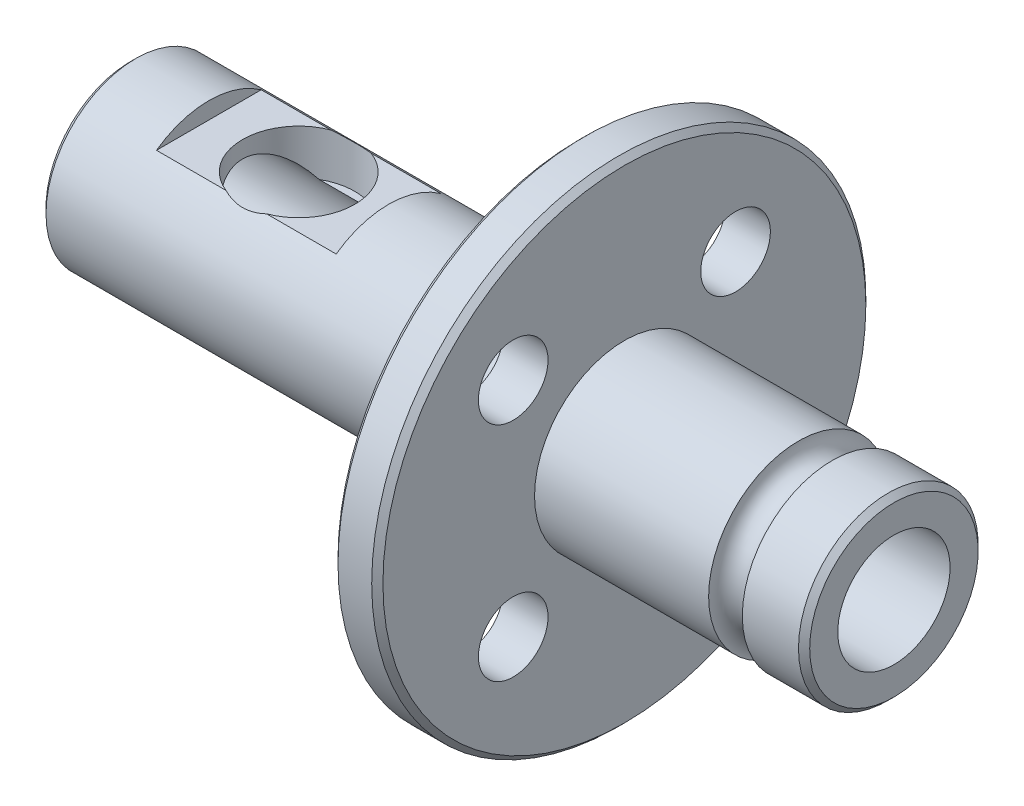
SolidWorks part; units mm, degrees
ref_plane "Front Plane" through (0, 0, 0) normal (0, 0, 1) x (1, 0, 0)
ref_plane "Top Plane" through (0, 0, 0) normal (0, 1, 0) x (1, 0, 0)
ref_plane "Right Plane" through (0, 0, 0) normal (1, 0, 0) x (0, 0, -1)
sketch "Sketch1" plane through (0, 0, 0) normal (0, 0, 1) x (1, 0, 0)
  line L0 (0, 0) -> (34, 0) construction
  line L1 (34, 0) -> (34, 4)
  line L2 (34, 4) -> (31.25, 4)
  line L3 (29.75, 4) -> (22, 4)
  line L4 (22, 4) -> (22, 11)
  line L5 (22, 11) -> (20, 11)
  line L6 (20, 11) -> (20, 4)
  line L7 (20, 4) -> (0, 4)
  line L8 (0, 4) -> (0, 0)
  line L9 (0, 0) -> (34, 0)
  arc A0 (31.25, 4) -> (29.75, 4) centre (30.5, 4) cw
  dimension "D7" = 0.75
  dimension "D1" = 4
  dimension "D2" = 34
  dimension "D3" = 12
  dimension "D4" = 2
  dimension "D5" = 11
  dimension "D6" = 2.75
revolve "Revolve1" add sketch "Sketch1" angle 360 about L0
sketch "Sketch2" plane through (34, 0, 0) normal (1, 0, 0) x (0, 0, -1)
  circle A0 centre (0, 0) radius 2.5
  dimension "D1" = 5
extrude "Cut-Extrude1" cut sketch "Sketch2" against normal through all
sketch "Sketch3" plane through (22, 0, 0) normal (1, 0, 0) x (0, 0, -1)
  line L0 (0, 7) -> (0, 0) construction
  line L1 (0, 0) -> (4.9497, 4.9497) construction
  circle A0 centre (0, 0) radius 7 construction
  circle A1 centre (4.9497, 4.9497) radius 1.55
  circle A2 centre (4.9497, -4.9497) radius 1.55
  circle A3 centre (-4.9497, -4.9497) radius 1.55
  circle A4 centre (-4.9497, 4.9497) radius 1.55
  point P15 (0, 0)
  dimension "D1" = 14
  dimension "D2" = 45
  dimension "D3" = 3.1
  dimension "D4" = 4
extrude "Cut-Extrude2" cut sketch "Sketch3" against normal through all both and the other way through all
ref_plane "Plane1" through (0, 4, 0) normal (0, 1, 0) x (1, 0, 0)
sketch "Sketch4" plane through (0, 4, 0) normal (0, 1, 0) x (1, 0, 0)
  line L1 (3.5, 2.5) -> (11.5, 2.5)
  line L2 (3.5, 2.5) -> (3.5, -2.5)
  line L3 (3.5, -2.5) -> (11.5, -2.5)
  line L4 (11.5, 2.5) -> (11.5, -2.5)
  line L5 (3.5, 2.5) -> (11.5, -2.5) construction
  line L6 (3.5, -2.5) -> (11.5, 2.5) construction
  point P0 (7.5, 0)
  dimension "D1" = 8
  dimension "D2" = 5
  dimension "D3" = 7.5
extrude "Cut-Extrude3" cut sketch "Sketch4" against normal blind 0.75
sketch "Sketch5" plane through (0, 3.25, 0) normal (0, 1, 0) x (1, 0, 0)
  circle A0 centre (7.5, 0) radius 2.5
  dimension "D1" = 5
  dimension "D2" = 7.5
extrude "Cut-Extrude4" cut sketch "Sketch5" against normal blind 2
chamfer "Chamfer1" distance 0.25 angle 45 4 edges at (34, 0, 4) (0, 0, 4) (22, 0, 11) (20, 0, 11)
